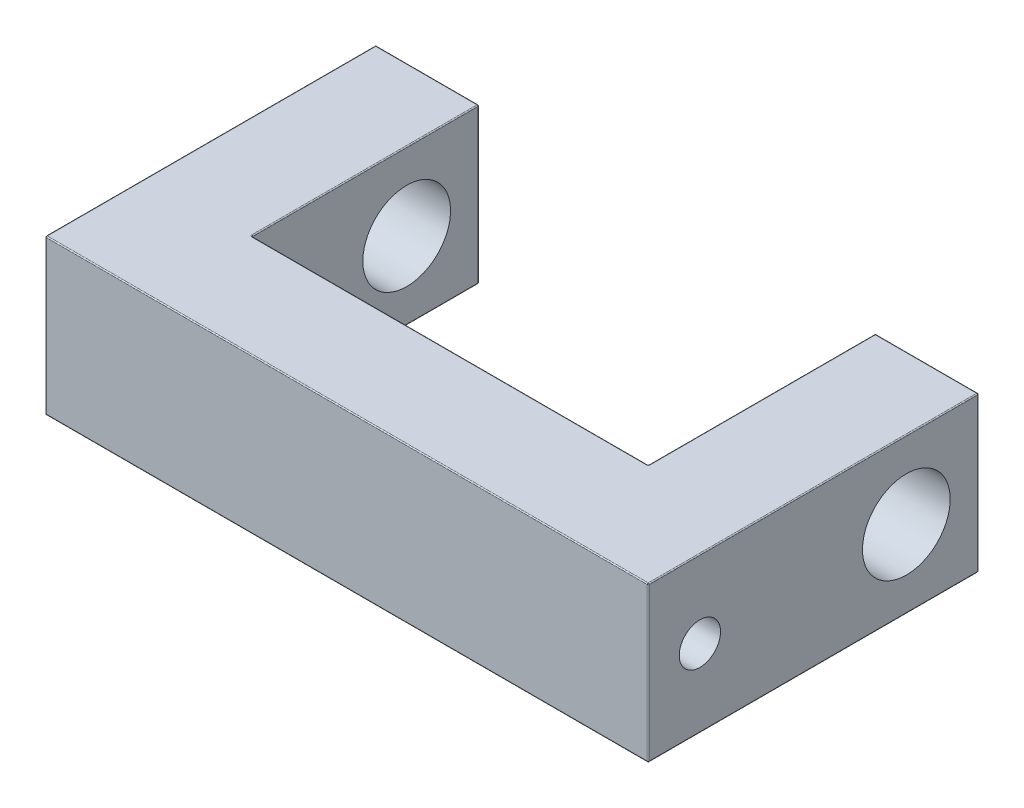
SolidWorks part; units mm, degrees
ref_plane "Front" through (0, 0, 0) normal (0, 0, 1) x (1, 0, 0)
ref_plane "Top" through (0, 0, 0) normal (0, 1, 0) x (1, 0, 0)
ref_plane "Right" through (0, 0, 0) normal (1, 0, 0) x (0, 0, -1)
sketch "Sketch1" plane through (0, 0, 0) normal (0, 1, 0) x (1, 0, 0)
  line L0 (48.4, 32) -> (58.4, 32)
  line L1 (0, 0) -> (58.4, 0)
  line L2 (0, 0) -> (0, 32)
  line L3 (0, 32) -> (10, 32)
  line L4 (58.4, 0) -> (58.4, 32)
  line L6 (10, 32) -> (10, 10)
  line L7 (10, 10) -> (48.4, 10)
  line L8 (48.4, 32) -> (48.4, 10)
  dimension "D1" = 58.4
  dimension "D2" = 10
  dimension "D3" = 10
  dimension "D4" = 22
  dimension "D5" = 32
extrude "Boss-Extrude1" add sketch "Sketch1" along normal blind 15
sketch "Sketch2" plane through (0, 0, 0) normal (-1, 0, 0) x (0, 0, 1)
  line L0 (-32, 15) -> (-32, 0) construction
  circle A0 centre (-25, 7.5) radius 4.25
  point P4 (-32, 7.5)
  dimension "D2" = 8.5
  dimension "D1" = 7
extrude "Cut-Extrude1" cut sketch "Sketch2" against normal through all
sketch "Sketch3" plane through (0, 0, 0) normal (-1, 0, 0) x (0, 0, 1)
  line L0 (0, 15) -> (0, 0) construction
  circle A0 centre (-5, 7.5) radius 2
  point P5 (0, 7.5)
  dimension "D1" = 4
  dimension "D2" = 5
extrude "Cut-Extrude2" cut sketch "Sketch3" against normal blind 7
sketch "Sketch4" plane through (58.4, 0, 0) normal (1, 0, 0) x (0, 0, -1)
  circle A0 centre (5, 7.5) radius 2 construction
  circle A1 centre (5, 7.5) radius 2
extrude "Cut-Extrude3" cut sketch "Sketch4" against normal blind 7
fillet "Fillet1" radius 0.1 24 edges at (48.4, 0, -21) (10, 0, -21) (10, 7.5, -32) (5, 15, -32) (0, 7.5, -32) (5, 0, -32) (48.4, 7.5, -10) (29.2, 15, -10) (10, 7.5, -10) (29.2, 0, -10) (58.4, 7.5, -32) (53.4, 15, -32) (48.4, 7.5, -32) (53.4, 0, -32) (48.4, 15, -21) (10, 15, -21) (0, 7.5, 0) (58.4, 7.5, 0) (58.4, 15, -16) (58.4, 0, -16) (0, 0, -16) (29.2, 0, 0) (29.2, 15, 0) (0, 15, -16)
